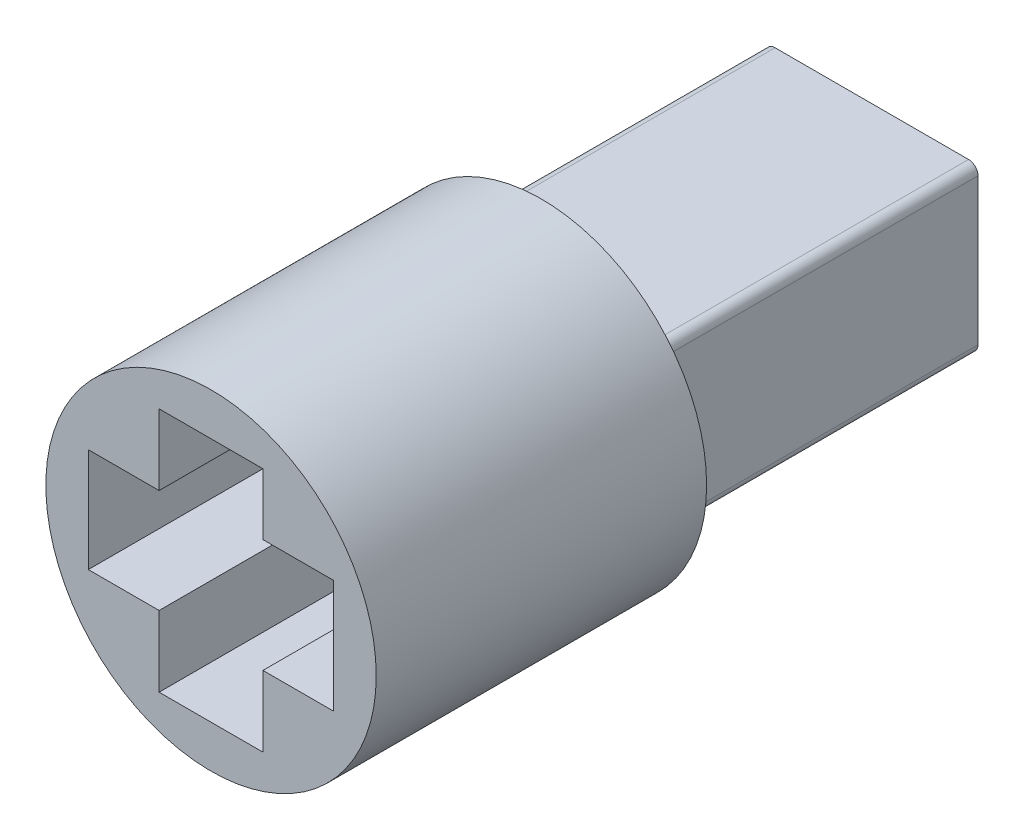
SolidWorks part; units mm, degrees
ref_plane "Front Plane" through (0, 0, 0) normal (1, 0, 0) x (0, 1, 0)
ref_plane "Top Plane" through (0, 0, 0) normal (0, 0, 1) x (0, 1, 0)
ref_plane "Right Plane" through (0, 0, 0) normal (0, 1, 0) x (-1, 0, 0)
sketch "Sketch2" plane through (0, 0, 0) normal (0, 0, 1) x (0, 1, 0)
  line L0 (0, 0) -> (3.5, 0)
  line L1 (3.5, 0) -> (3.5, 4.5)
  line L2 (3.5, 4.5) -> (0, 4.5)
  line L3 (0, 4.5) -> (0, 0)
extrude "Boss-Extrude1" add sketch "Sketch2" along normal blind 7
sketch "Sketch3" plane through (0, 0, 7) normal (0, 0, 1) x (1, 0, 0)
  circle A0 centre (-2.25, 1.75) radius 3.5
extrude "Boss-Extrude2" add sketch "Sketch3" along normal blind 7 contours A0
sketch "Sketch4" plane through (0, 0, 14) normal (0, 0, 1) x (1, 0, 0)
  line L4 (-3.35, 2.85) -> (-4.85, 2.85)
  line L5 (-3.35, 2.85) -> (-3.35, 4.35)
  line L7 (-1.15, 0.65) -> (-1.15, -0.85)
  line L12 (-1.15, 0.65) -> (0.35, 0.65)
  line L13 (-4.85, 0.65) -> (-3.35, 0.65)
  line L14 (-3.35, 0.65) -> (-3.35, -0.85)
  line L17 (-1.15, 4.35) -> (-1.15, 3.05)
  line L18 (-1.15, 3.05) -> (0.35, 3.05)
  line L20 (-4.85, 2.85) -> (-4.85, 0.65)
  line L21 (-3.35, -0.85) -> (-1.15, -0.85)
  line L22 (0.35, 0.65) -> (0.35, 3.05)
  line L23 (-3.35, 4.35) -> (-1.15, 4.35)
extrude "Cut-Extrude1" cut sketch "Sketch4" against normal blind 5 contours L7 L21 L14 L13 L20 L4 L5 L23 L17 L18 L22 L12
fillet "Fillet1" radius 0.2 1 edges at (0, 3.5, 3.5)
fillet "Fillet2" radius 0.2 3 edges at (-4.5, 0, 3.5) (0, 0, 3.5) (-4.5, 3.5, 3.5)
